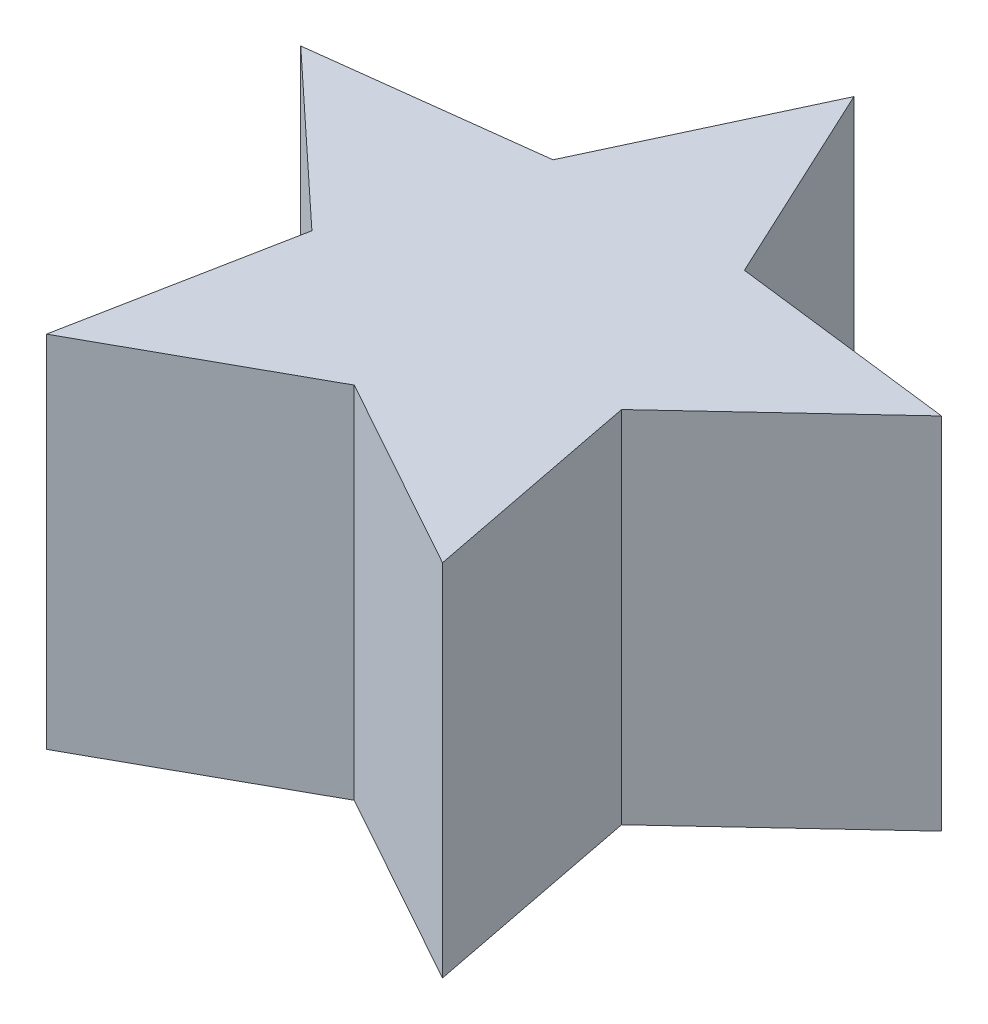
SolidWorks part; units mm, degrees
ref_plane "Front Plane" through (0, 0, 0) normal (0, 0, 1) x (1, 0, 0)
ref_plane "Top Plane" through (0, 0, 0) normal (0, 1, 0) x (1, 0, 0)
ref_plane "Right Plane" through (0, 0, 0) normal (1, 0, 0) x (0, 0, -1)
sketch "Sketch1" plane through (0, 0, 0) normal (0, 1, 0) x (1, 0, 0)
  line L0 (0, 8.9) -> (0, 0) construction
  line L1 (0, 8.9) -> (-8.4644, 2.7503) construction
  line L2 (-8.4644, 2.7503) -> (-5.2313, -7.2003) construction
  line L3 (-5.2313, -7.2003) -> (5.2313, -7.2003) construction
  line L4 (5.2313, -7.2003) -> (8.4644, 2.7503) construction
  line L5 (8.4644, 2.7503) -> (0, 8.9) construction
  line L6 (0, 8.9) -> (2.5278, 3.4792)
  line L7 (2.5278, 3.4792) -> (8.4644, 2.7503)
  line L8 (8.4644, 2.7503) -> (4.09, -1.3289)
  line L9 (4.09, -1.3289) -> (5.2313, -7.2003)
  line L10 (5.2313, -7.2003) -> (0, -4.3005)
  line L11 (0, -4.3005) -> (-5.2313, -7.2003)
  line L12 (-5.2313, -7.2003) -> (-4.09, -1.3289)
  line L13 (-4.09, -1.3289) -> (-8.4644, 2.7503)
  line L14 (-8.4644, 2.7503) -> (-2.5278, 3.4792)
  line L15 (-2.5278, 3.4792) -> (0, 8.9)
  circle A0 centre (0, 0) radius 7.2003 construction
  dimension "D1" = 50
  dimension "D2" = 8.9
extrude "Boss-Extrude1" add sketch "Sketch1" along normal blind 9.5
